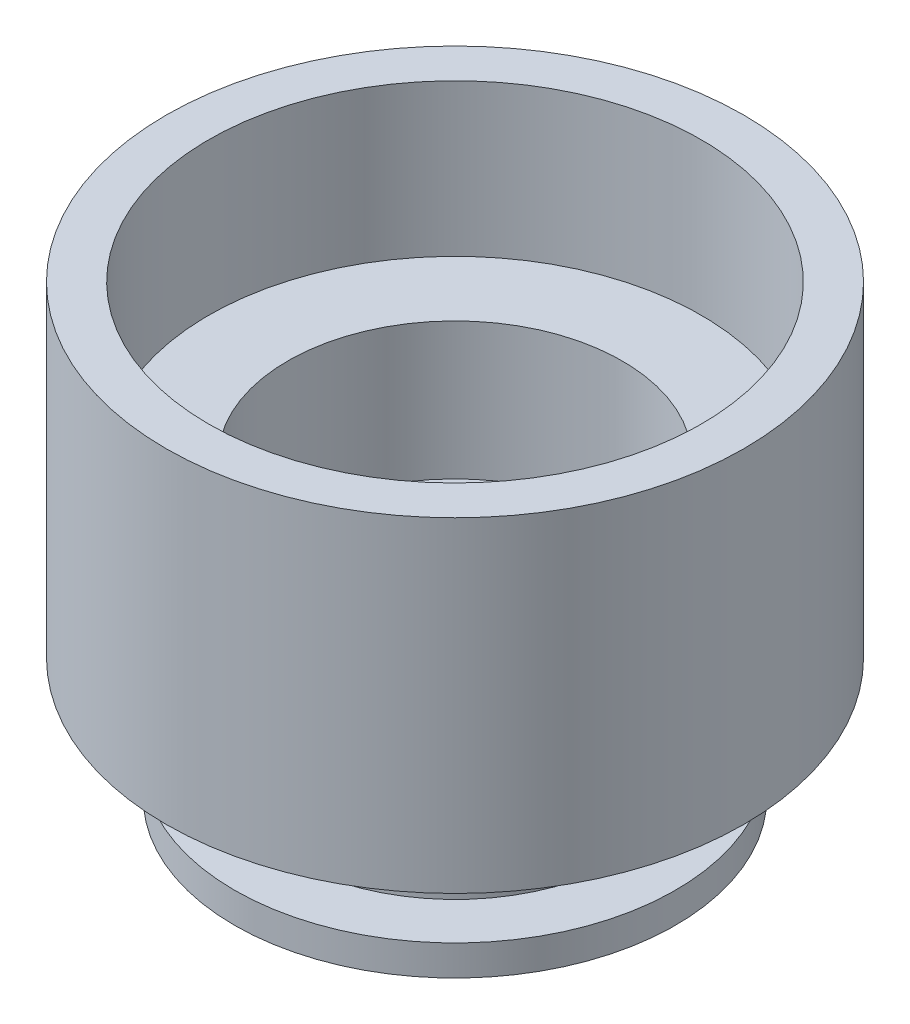
SolidWorks part; units mm, degrees
ref_plane "Front Plane" through (0, 0, 0) normal (0, 0, 1) x (1, 0, 0)
ref_plane "Top Plane" through (0, 0, 0) normal (0, 1, 0) x (1, 0, 0)
ref_plane "Right Plane" through (0, 0, 0) normal (1, 0, 0) x (0, 0, -1)
sketch "Sketch1" plane through (0, 0, 0) normal (0, 1, 0) x (1, 0, 0)
  circle A0 centre (0, 0) radius 7.25
  dimension "D1" = 14.5
extrude "Boss-Extrude1" add sketch "Sketch1" along normal blind 1
sketch "Sketch2" plane through (0, 1, 0) normal (0, 1, 0) x (1, 0, 0)
  circle A0 centre (0, 0) radius 5.5
  dimension "D1" = 11
extrude "Boss-Extrude2" add sketch "Sketch2" along normal blind 3
sketch "Sketch3" plane through (0, 4, 0) normal (0, 1, 0) x (1, 0, 0)
  circle A0 centre (0, 0) radius 9.5
  dimension "D1" = 19
extrude "Boss-Extrude3" add sketch "Sketch3" along normal blind 1.2
sketch "Sketch4" plane through (0, 5.2, 0) normal (0, 1, 0) x (1, 0, 0)
  circle A0 centre (0, 0) radius 9.5
  circle A1 centre (0, 0) radius 5.5
  dimension "D1" = 11
  dimension "D2" = 19
extrude "Boss-Extrude4" add sketch "Sketch4" along normal blind 4.5
sketch "Sketch5" plane through (0, 9.7, 0) normal (0, 1, 0) x (1, 0, 0)
  circle A0 centre (0, 0) radius 9.5
  circle A1 centre (0, 0) radius 8.1
  dimension "D1" = 19
  dimension "D2" = 16.2
extrude "Boss-Extrude5" add sketch "Sketch5" along normal blind 5
